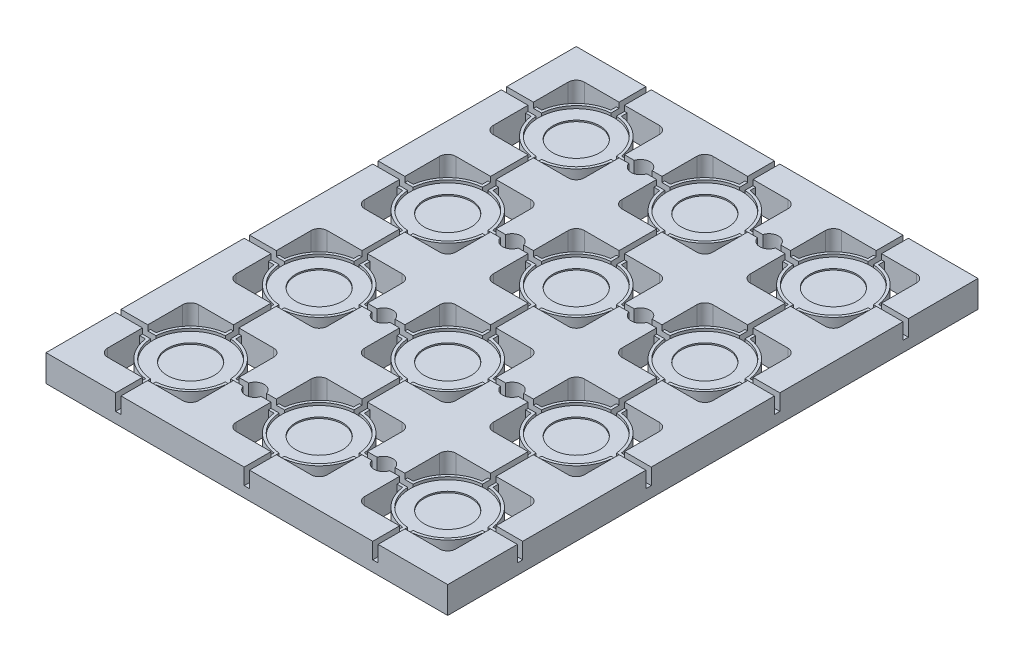
SolidWorks part; units mm, degrees
ref_plane "Front Plane" through (0, 0, 0) normal (0, 0, 1) x (1, 0, 0)
ref_plane "Top Plane" through (0, 0, 0) normal (0, 1, 0) x (1, 0, 0)
ref_plane "Right Plane" through (0, 0, 0) normal (1, 0, 0) x (0, 0, -1)
sketch "Sketch1" plane through (0, 0, 0) normal (0, 1, 0) x (1, 0, 0)
  line L6 (-75, -99) -> (75, -99)
  line L11 (-75, -99) -> (-75, 99)
  line L12 (-75, 99) -> (75, 99)
  line L76 (75, -99) -> (75, 99)
  line L77 (-75, -99) -> (75, 99) construction
  line L78 (-75, 99) -> (75, -99) construction
  point P0 (0, 0)
  dimension "D1" = 150
  dimension "D2" = 198
extrude "Boss-Extrude1" add sketch "Sketch1" along normal blind 10
sketch "Sketch2" plane through (0, 10, 0) normal (0, 1, 0) x (1, 0, 0)
  line L0 (75, 99) -> (-75, 99) construction
  line L1 (-75, 99) -> (-75, -99) construction
  line L2 (-62, 55) -> (-34, 55)
  line L3 (-65, 58) -> (-65, 86)
  line L4 (-62, 89) -> (-34, 89)
  line L5 (-31, 58) -> (-31, 86)
  line L6 (-65, 55) -> (-31, 89) construction
  line L7 (-65, 89) -> (-31, 55) construction
  line L8 (-33, 72) -> (-31, 72) construction
  line L9 (-33.1339, 70) -> (-31, 70)
  line L10 (-33.1339, 74) -> (-31, 74)
  line L11 (-33, 74) -> (-31, 74) construction
  line L12 (-33, 70) -> (-31, 70) construction
  line L13 (-46, 57.1339) -> (-46, 55)
  line L14 (-50, 57.1339) -> (-50, 55)
  line L15 (-62.8661, 70) -> (-65, 70)
  line L16 (-62.8661, 74) -> (-65, 74)
  line L17 (-50, 86.8661) -> (-50, 89)
  line L18 (-46, 86.8661) -> (-46, 89)
  arc A0 (-50, 86.8661) -> (-62.8661, 74) centre (-48, 72) ccw
  arc A1 (-62.8661, 70) -> (-50, 57.1339) centre (-48, 72) ccw
  arc A2 (-46, 57.1339) -> (-33.1339, 70) centre (-48, 72) ccw
  arc A3 (-33.1339, 74) -> (-46, 86.8661) centre (-48, 72) ccw
  arc A4 (-62, 55) -> (-65, 58) centre (-62, 58) cw
  arc A5 (-65, 86) -> (-62, 89) centre (-62, 86) cw
  arc A6 (-34, 55) -> (-31, 58) centre (-34, 58) ccw
  arc A7 (-34, 89) -> (-31, 86) centre (-34, 86) cw
  point P4 (-48, 72)
  dimension "D3" = 30
  dimension "D8" = 3
  dimension "D1" = 34
  dimension "D2" = 10
  dimension "D7" = 10
  dimension "D4" = 2
  dimension "D5" = 2
  dimension "D6" = 4
extrude "Cut-Extrude2" cut sketch "Sketch2" against normal through all contours A3 L10 L5 L4 L18 | A2 L13 L2 L5 L9 | A1 L15 L3 L2 L14 | A0 L17 L4 L3 L16
sketch "Sketch3" plane through (0, 10, 0) normal (0, 1, 0) x (1, 0, 0)
  line L0 (-31, 58) -> (-31, 86) construction
  line L1 (-62, 55) -> (-34, 55) construction
  line L2 (-65, 58) -> (-65, 86) construction
  line L3 (-62, 89) -> (-34, 89) construction
  line L4 (-31, 58) -> (-31, 86)
  line L5 (-62, 55) -> (-34, 55)
  line L6 (-65, 58) -> (-65, 86)
  line L7 (-62, 89) -> (-34, 89)
  arc A0 (-31, 86) -> (-34, 89) centre (-34, 86) ccw construction
  arc A1 (-34, 55) -> (-31, 58) centre (-34, 58) ccw construction
  arc A2 (-65, 58) -> (-62, 55) centre (-62, 58) ccw construction
  arc A3 (-62, 89) -> (-65, 86) centre (-62, 86) ccw construction
  arc A4 (-31, 86) -> (-34, 89) centre (-34, 86) ccw
  arc A5 (-34, 55) -> (-31, 58) centre (-34, 58) ccw
  arc A6 (-65, 58) -> (-62, 55) centre (-62, 58) ccw
  arc A7 (-62, 89) -> (-65, 86) centre (-62, 86) ccw
extrude "Cut-Extrude3" cut sketch "Sketch3" against normal blind 2
sketch "Sketch4" plane through (0, 8, 0) normal (0, 1, 0) x (1, 0, 0)
  circle A0 centre (-48, 72) radius 14
  dimension "D1" = 28
extrude "Cut-Extrude4" cut sketch "Sketch4" against normal blind 1
sketch "Sketch5" plane through (0, 10, 0) normal (0, 1, 0) x (1, 0, 0)
  line L0 (-75, 72) -> (-21, 72) construction
  line L2 (-48, 99) -> (-48, 86) construction
  line L3 (75, 99) -> (-75, 99) construction
  line L4 (-75, 99) -> (-75, -99) construction
  line L5 (-62, 89) -> (-34, 89) construction
  line L8 (-49, 99) -> (-49, 85.9642)
  line L9 (-75, 71) -> (-61.9642, 71)
  line L10 (-47, 99) -> (-47, 85.9642)
  line L11 (-75, 73) -> (-61.9642, 73)
  line L12 (-49, 99) -> (-47, 99)
  line L14 (-75, 71) -> (-75, 73)
  line L16 (-34.0358, 73) -> (-21, 73)
  line L20 (-34.0358, 71) -> (-21, 71)
  line L22 (-47, 58.0358) -> (-47, 45)
  line L23 (-47, 99) -> (-47, -100) construction
  line L24 (-48, 58) -> (-48, 45) construction
  line L25 (-48, 99) -> (-48, -100) construction
  line L26 (-49, 58.0358) -> (-49, 45)
  line L27 (-49, 99) -> (-49, -100) construction
  line L28 (-31, 58) -> (-31, 86) construction
  line L29 (-49, 99) -> (-47, 99)
  line L32 (-75, 73) -> (-75, 71)
  line L33 (-49, 45) -> (-47, 45)
  line L34 (-21, 73) -> (-21, 71)
  line L35 (-62, 55) -> (-34, 55) construction
  circle A0 centre (-48, 72) radius 14 construction
  arc A1 (-47, 85.9642) -> (-49, 85.9642) centre (-48, 72) ccw
  arc A2 (-61.9642, 73) -> (-61.9642, 71) centre (-48, 72) ccw
  arc A3 (-34.0358, 71) -> (-34.0358, 73) centre (-48, 72) ccw
  arc A4 (-49, 58.0358) -> (-47, 58.0358) centre (-48, 72) ccw
  point P9 (-48, 89)
  point P13 (-75, 72)
  point P14 (-62.9642, 74)
  point P15 (-22, 73)
  line M4 (75, 99) -> (-75, 99)
  line M5 (-75, 99) -> (-75, -99)
  line M7 (-34, 55) -> (-62, 55)
  line M8 (-65, 58) -> (-65, 86)
  line M9 (-62, 89) -> (-34, 89)
  line M10 (-31, 86) -> (-31, 58)
  dimension "D1" = 0
  dimension "D2" = 1
  dimension "D4" = 10
  dimension "D5" = 10
  dimension "D6" = 2
  dimension "D3" = 1
extrude "Cut-Extrude5" cut sketch "Sketch5" against normal blind 6 contours L26 L33 L22 M7 | A4 L26 L22 M7 | L34 L16 L20 M10 | A3 L20 L16 M10 | A1 L10 L8 M9 | L10 L8 M4 M9 | L11 L9 M5 M8 | A2 L11 L9 M8
sketch "Sketch7" plane through (0, 7, 0) normal (0, 1, 0) x (1, 0, 0)
  circle A0 centre (-48, 72) radius 8.75
  dimension "D1" = 17.5
extrude "Cut-Extrude7" cut sketch "Sketch7" against normal blind 0.5
pattern_linear "LPattern2" count 3 spacing 48 along (1, 0, 0) count 4 spacing 48 along (0, 0, 1) of "Cut-Extrude2", "Cut-Extrude3", "Cut-Extrude4", "Cut-Extrude5", "Cut-Extrude7"
sketch "Sketch9" plane through (0, 10, 0) normal (0, 1, 0) x (1, 0, 0)
  line L0 (-24, 73) -> (-24, 71) construction
  line L1 (-31, 73) -> (-17, 73) construction
  line L2 (-31, 71) -> (-17, 71) construction
  circle A0 centre (-24, 72) radius 3.5
  dimension "D1" = 7
extrude "Cut-Extrude9" cut sketch "Sketch9" against normal through all
pattern_linear "LPattern3" count 2 spacing 48 along (1, 0, 0) count 4 spacing 48 along (0, 0, 1) of "Cut-Extrude9"
